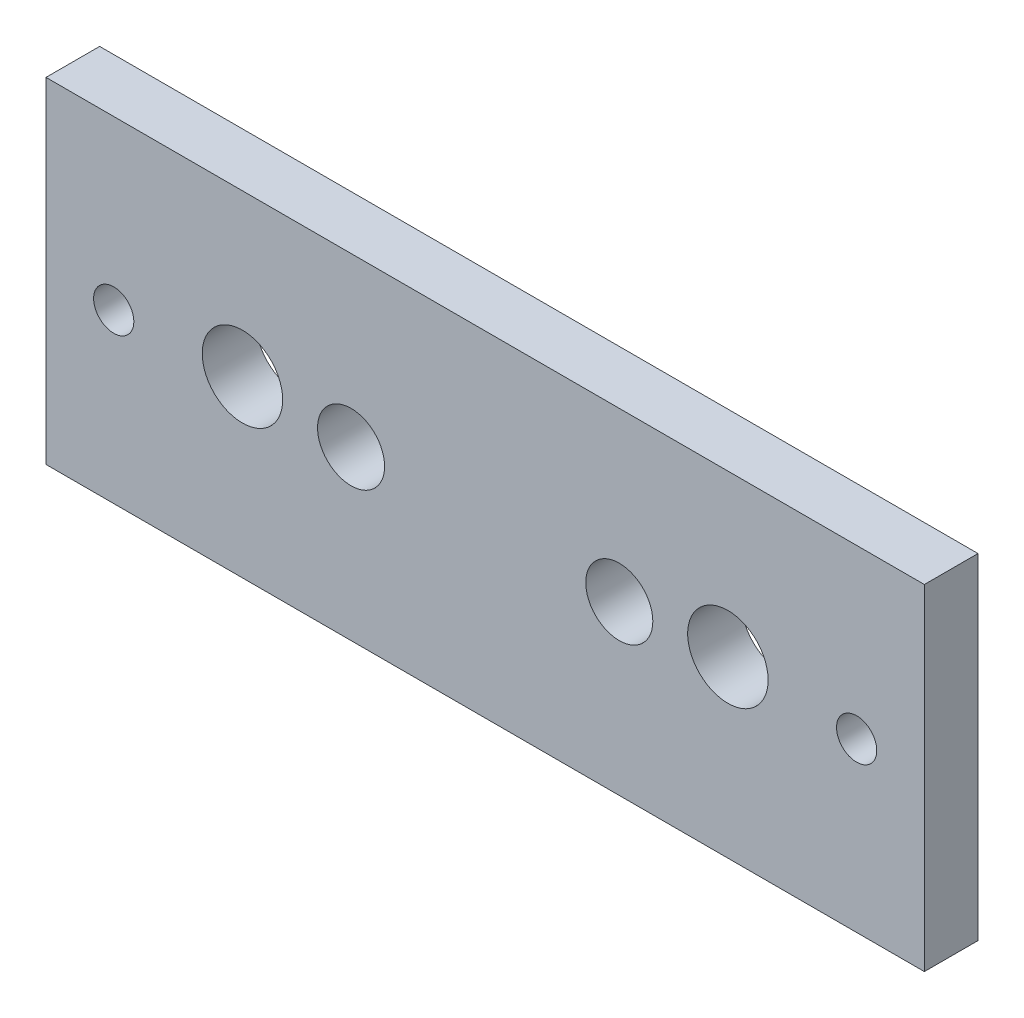
SolidWorks part; units mm, degrees
ref_plane "Płaszczyzna przednia" through (0, 0, 0) normal (0, 0, 1) x (1, 0, 0)
ref_plane "Płaszczyzna górna" through (0, 0, 0) normal (0, 1, 0) x (1, 0, 0)
ref_plane "Płaszczyzna prawa" through (0, 0, 0) normal (1, 0, 0) x (0, 0, -1)
sketch "Sketch1" plane through (0, 0, 0) normal (0, 0, 1) x (1, 0, 0)
  line L1 (0, 0) -> (65.5, 0)
  line L2 (0, 0) -> (0, 25)
  line L3 (0, 25) -> (65.5, 25)
  line L4 (65.5, 0) -> (65.5, 25)
  dimension "D1" = 65.5
  dimension "D2" = 25
extrude "Boss-Extrude1" add sketch "Sketch1" along normal blind 4
hole_wizard "Ø5.0mm Dowel Hole1" positions "Sketch2" profile "Sketch3" hole size "Ø5.0" standard "ANSI Metric" end condition through all
sketch "Sketch2" plane through (0, 0, 4) normal (0, 0, 1) x (1, 0, 0)
  line L0 (0, 0) -> (65.5, 0) construction
  line L1 (0, 25) -> (0, 0) construction
  point P0 (22.75, 12.5)
  point P2 (42.75, 12.5)
  dimension "D1" = 12.5
  dimension "D2" = 22.75
  dimension "D3" = 20
sketch "Sketch3" plane through (22.75, 12.5, 4) normal (1, 0, 0) x (0, -1, 0)
  line L0 (0, 0) -> (0, 4)
  line L1 (0, 4) -> (2.5, 4)
  line L2 (2.5, 4) -> (2.5, 0)
  line L5 (2.5, 0) -> (0, 0)
  line L11 (0, -6.35) -> (0, 107.95) construction
  dimension "Thru Hole Dia." = 5
  dimension "Thru Hole Depth" = 4
sketch "Sketch4" plane through (0, 0, 4) normal (0, 0, 1) x (1, 0, 0)
  line L0 (65.5, 25) -> (0, 25) construction
  line L1 (0, 25) -> (0, 0) construction
  circle A0 centre (14.65, 13) radius 3
  circle A1 centre (50.85, 13) radius 3
  dimension "D1" = 6
  dimension "D2" = 6
  dimension "D3" = 36.2
  dimension "D4" = 12
  dimension "D5" = 14.65
extrude "Cut-Extrude1" cut sketch "Sketch4" against normal through all
hole_wizard "Ø3.0mm Dowel Hole1" positions "Sketch5" profile "Sketch6" hole size "Ø3.0" standard "ANSI Metric" end condition through all
sketch "Sketch5" plane through (0, 0, 4) normal (0, 0, 1) x (1, 0, 0)
  line L0 (0, 25) -> (0, 0) construction
  line L1 (65.5, 25) -> (0, 25) construction
  line L2 (65.5, 0) -> (65.5, 25) construction
  point P0 (5.05, 12.5)
  point P2 (60.45, 12.5)
  dimension "D1" = 5.05
  dimension "D2" = 12.5
  dimension "D3" = 5.05
sketch "Sketch6" plane through (5.05, 12.5, 4) normal (1, 0, 0) x (0, -1, 0)
  line L0 (0, 0) -> (0, 4)
  line L1 (0, 4) -> (1.5, 4)
  line L2 (1.5, 4) -> (1.5, 0)
  line L5 (1.5, 0) -> (0, 0)
  line L11 (0, -6.35) -> (0, 107.95) construction
  dimension "Thru Hole Dia." = 3
  dimension "Thru Hole Depth" = 4
